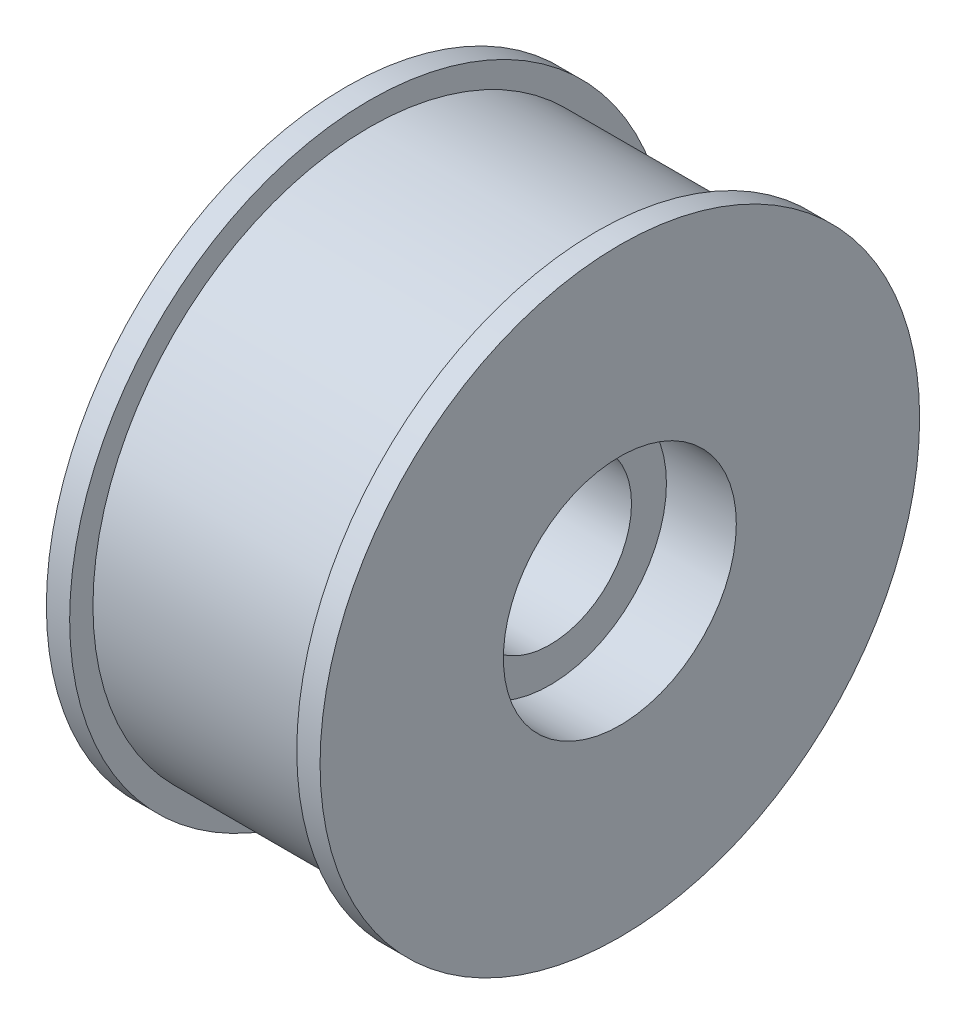
SolidWorks part; units mm, degrees
ref_plane "Front Plane" through (0, 0, 0) normal (0, 0, 1) x (1, 0, 0)
ref_plane "Top Plane" through (0, 0, 0) normal (0, 1, 0) x (1, 0, 0)
ref_plane "Right Plane" through (0, 0, 0) normal (1, 0, 0) x (0, 0, -1)
sketch "Sketch2" plane through (0, 0, 0) normal (0, 0, 1) x (1, 0, 0)
  line L0 (0, 0) -> (0, 12.87)
  line L1 (0, 12.87) -> (1, 12.87)
  line L2 (1, 12.87) -> (1, 11.87)
  line L3 (1, 11.87) -> (10.75, 11.87)
  line L4 (10.75, 11.87) -> (10.75, 12.87)
  line L5 (10.75, 12.87) -> (11.75, 12.87)
  line L6 (11.75, 12.87) -> (11.75, 0)
  line L7 (11.75, 0) -> (0, 0)
  dimension "D1" = 11.87
  dimension "D2" = 9.75
  dimension "D3" = 1
  dimension "D4" = 1
  dimension "D5" = 1
  dimension "D6" = 1
revolve "Revolve1" add sketch "Sketch2" angle 360 about L7
sketch "Sketch3" plane through (11.75, 0, 0) normal (1, 0, 0) x (0, 0, -1)
  circle A0 centre (0, 0) radius 5
  dimension "D1" = 10
extrude "Cut-Extrude1" cut sketch "Sketch3" against normal blind 3
sketch "Sketch4" plane through (0, 0, 0) normal (-1, 0, 0) x (0, 0, 1)
  circle A0 centre (0, 0) radius 5
  dimension "D1" = 10
extrude "Cut-Extrude2" cut sketch "Sketch4" against normal blind 3
sketch "Sketch5" plane through (8.75, 0, 0) normal (1, 0, 0) x (0, 0, -1)
  circle A0 centre (0, 0) radius 3.5
  dimension "D1" = 7
extrude "Cut-Extrude3" cut sketch "Sketch5" against normal through all
